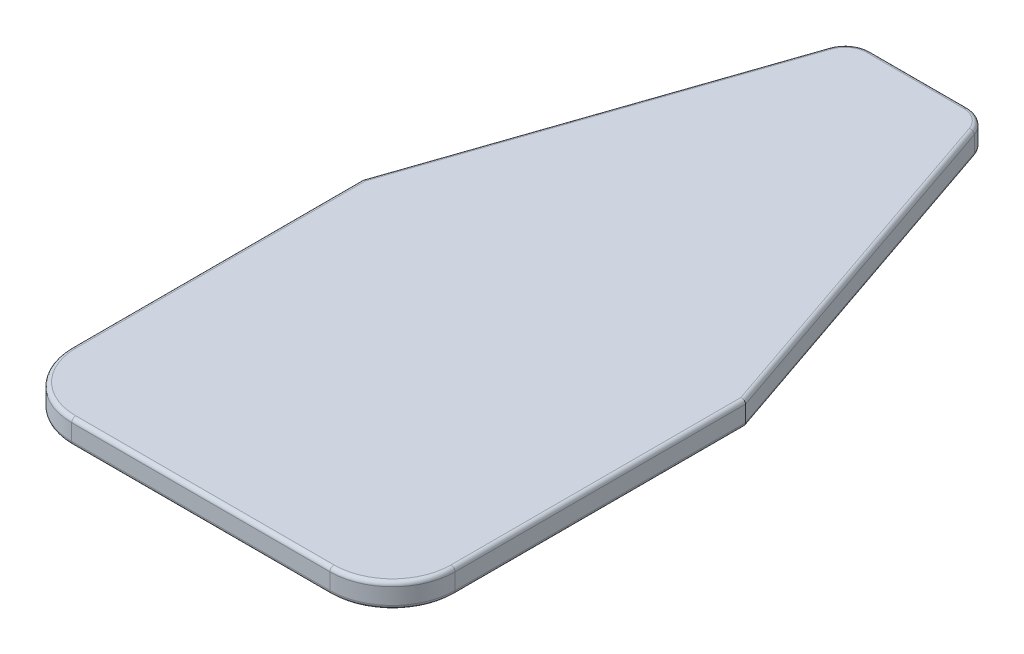
SolidWorks part; units mm, degrees
ref_plane "Front Plane" through (0, 0, 0) normal (0, 0, 1) x (1, 0, 0)
ref_plane "Top Plane" through (0, 0, 0) normal (0, 1, 0) x (1, 0, 0)
ref_plane "Right Plane" through (0, 0, 0) normal (1, 0, 0) x (0, 0, -1)
sketch "Sketch1" plane through (0, 0, 0) normal (0, 1, 0) x (1, 0, 0)
  line L0 (-101.6, -24.3645) -> (101.6, -24.3645)
  line L1 (-38.1, 540.7855) -> (38.1, 540.7855)
  line L2 (0, 540.7855) -> (0, -24.3645) construction
  line L3 (150.8125, 253.448) -> (57.15, 527.1697)
  line L4 (-150.8125, 253.448) -> (-57.15, 527.1697)
  line L5 (-150.8125, 253.448) -> (0, 253.448) construction
  line L6 (150.8125, 253.448) -> (0, 253.448) construction
  line L7 (-150.8125, 24.848) -> (-150.8125, 253.448)
  line L8 (150.8125, 24.848) -> (150.8125, 253.448)
  line L9 (-150.8125, 24.848) -> (0, 24.848) construction
  line L10 (150.8125, 24.848) -> (0, 24.848) construction
  arc A0 (101.6, -24.3645) -> (150.8125, 24.848) centre (101.6, 24.848) ccw
  arc A1 (-150.8125, 24.848) -> (-101.6, -24.3645) centre (-101.6, 24.848) ccw
  arc A2 (57.15, 527.1697) -> (38.1, 540.7855) centre (38.1, 520.6511) ccw
  arc A3 (-38.1, 540.7855) -> (-57.15, 527.1697) centre (-38.1, 520.6511) ccw
  dimension "D2" = 114.3
  dimension "D6" = 76.2
  dimension "D7" = 49.2125
  dimension "D8" = 20.1344
  dimension "D1" = 203.2
  dimension "D3" = 228.6
  dimension "D4" = 565.15
  dimension "D5" = 301.625
extrude "Boss-Extrude1" add sketch "Sketch1" along normal blind 19.05
fillet "Fillet1" radius 3.175 10 edges at (-103.9813, 19.05, -390.3089) (-49.8078, 19.05, -537.0316) (0, 19.05, -540.7855) (49.8078, 19.05, -537.0316) (-150.8125, 19.05, -139.148) (-136.3985, 19.05, 9.9505) (0, 19.05, 24.3645) (136.3985, 19.05, 9.9505) (103.9812, 19.05, -390.3089) (150.8125, 19.05, -139.148)
fillet "Fillet2" radius 3.175 10 edges at (103.9812, 0, -390.3089) (49.8078, 0, -537.0316) (0, 0, -540.7855) (-49.8078, 0, -537.0316) (-150.8125, 0, -139.148) (-136.3985, 0, 9.9505) (150.8125, 0, -139.148) (136.3985, 0, 9.9505) (-103.9813, 0, -390.3089) (0, 0, 24.3645)
sketch "Sketch5" plane through (0, 19.05, 0) normal (0, 1, 0) x (1, 0, 0)
  line L0 (38.1, 537.6105) -> (-38.1, 537.6105) construction
  line L1 (0, -21.1895) -> (-0.003, 542.4026) construction
  line L2 (-43.3215, 507.7584) -> (43.3215, 507.7584) construction
  line L3 (-101.6, -21.1895) -> (101.6, -21.1895) construction
  line L4 (43.3215, 507.7584) -> (60.4365, 507.7584) construction
  line L5 (147.6375, 252.9198) -> (54.146, 526.1418) construction
  line L6 (-43.3215, 507.7584) -> (-60.4365, 507.7584) construction
  line L7 (-54.146, 526.1418) -> (-147.6375, 252.9198) construction
  line B0 (-35.109, 447.4484) -> (35.2377, 518.3442) construction
  line B1 (-35.1059, 518.2113) -> (35.109, 447.4484) construction
  arc B2 (-24.9328, 526.498) -> (24.9268, 526.498) centre (-0.003, 542.4026) ccw
  arc B3 (-43.3215, 507.7584) -> (-24.9328, 526.498) centre (7.5558, 476.2258) cw
  arc B4 (24.9268, 526.498) -> (43.3215, 507.7584) centre (-2.6466, 481.0344) cw
  arc B5 (43.3215, 507.7584) -> (43.2864, 457.8401) centre (60.0594, 482.7875) ccw
  arc B6 (43.2864, 457.8401) -> (24.9269, 439.51) centre (-3.0428, 485.8841) cw
  arc B7 (-24.9914, 439.5451) -> (-43.2864, 457.8401) centre (3.0881, 485.9196) cw
  arc B8 (-43.3215, 507.7584) -> (-43.2864, 457.8401) centre (-60.0645, 482.7875) cw
  arc B9 (-24.9914, 439.5451) -> (24.9269, 439.51) centre (-0.0437, 423.2596) cw
  circle B10 centre (-30.052, 512.8835) radius 2.25
  circle B11 centre (30.0521, 512.8835) radius 2.25
  circle B12 centre (30.0519, 452.7794) radius 2.25
  circle B13 centre (-30.0527, 452.7791) radius 2.25
  circle B14 centre (0.0248, 482.837) radius 12.27
  line B15 (37.184, 19.7525) -> (107.5307, 90.6482) construction
  line B16 (37.1872, 90.5154) -> (107.402, 19.7525) construction
  arc B17 (47.3603, 98.8021) -> (97.2199, 98.8021) centre (72.2901, 114.7066) ccw
  arc B18 (28.9715, 80.0624) -> (47.3603, 98.8021) centre (79.8488, 48.5298) cw
  arc B19 (97.2199, 98.8021) -> (115.6145, 80.0624) centre (69.6464, 53.3384) cw
  arc B20 (115.6145, 80.0624) -> (115.5794, 30.1441) centre (132.3525, 55.0915) ccw
  arc B21 (115.5794, 30.1441) -> (97.2199, 11.814) centre (69.2502, 58.1882) cw
  arc B22 (47.3016, 11.8491) -> (29.0066, 30.1441) centre (75.3812, 58.2237) cw
  arc B23 (28.9715, 80.0624) -> (29.0066, 30.1441) centre (12.2285, 55.0915) cw
  arc B24 (47.3016, 11.8491) -> (97.2199, 11.814) centre (72.2493, -4.4363) cw
  circle B25 centre (42.241, 85.1876) radius 2.25
  circle B26 centre (102.3451, 85.1876) radius 2.25
  circle B27 centre (102.3449, 25.0835) radius 2.25
  circle B28 centre (42.2403, 25.0832) radius 2.25
  circle B29 centre (72.3178, 55.1411) radius 12.27
  line B30 (-37.1844, 19.7521) -> (-107.5319, 90.6471) construction
  line B31 (-37.1883, 90.515) -> (-107.4025, 19.7514) construction
  arc B32 (-47.3615, 98.8016) -> (-97.2211, 98.8011) centre (-72.2915, 114.7059) cw
  arc B33 (-28.9726, 80.0621) -> (-47.3615, 98.8016) centre (-79.8496, 48.529) ccw
  arc B34 (-97.2211, 98.8011) -> (-115.6156, 80.0612) centre (-69.6472, 53.3377) ccw
  arc B35 (-115.6156, 80.0612) -> (-115.58, 30.1429) centre (-132.3533, 55.0901) cw
  arc B36 (-115.58, 30.1429) -> (-97.2203, 11.813) centre (-69.251, 58.1874) ccw
  arc B37 (-47.302, 11.8486) -> (-29.0072, 30.1438) centre (-75.382, 58.2229) ccw
  arc B38 (-28.9726, 80.0621) -> (-29.0072, 30.1438) centre (-12.2293, 55.0914) ccw
  arc B39 (-47.302, 11.8486) -> (-97.2203, 11.813) centre (-72.2495, -4.4371) ccw
  circle B40 centre (-42.2422, 85.1871) radius 2.25
  circle B41 centre (-102.3462, 85.1865) radius 2.25
  circle B42 centre (-102.3454, 25.0824) radius 2.25
  circle B43 centre (-72.3186, 55.1403) radius 12.27
  dimension "D1" = 11.1125
  dimension "D2" = 11.1125
sketch_block_instance "Block2-1"
sketch_block "Block2"
sketch_block_instance "Block2-6"
sketch_block_instance "Block2-7"
